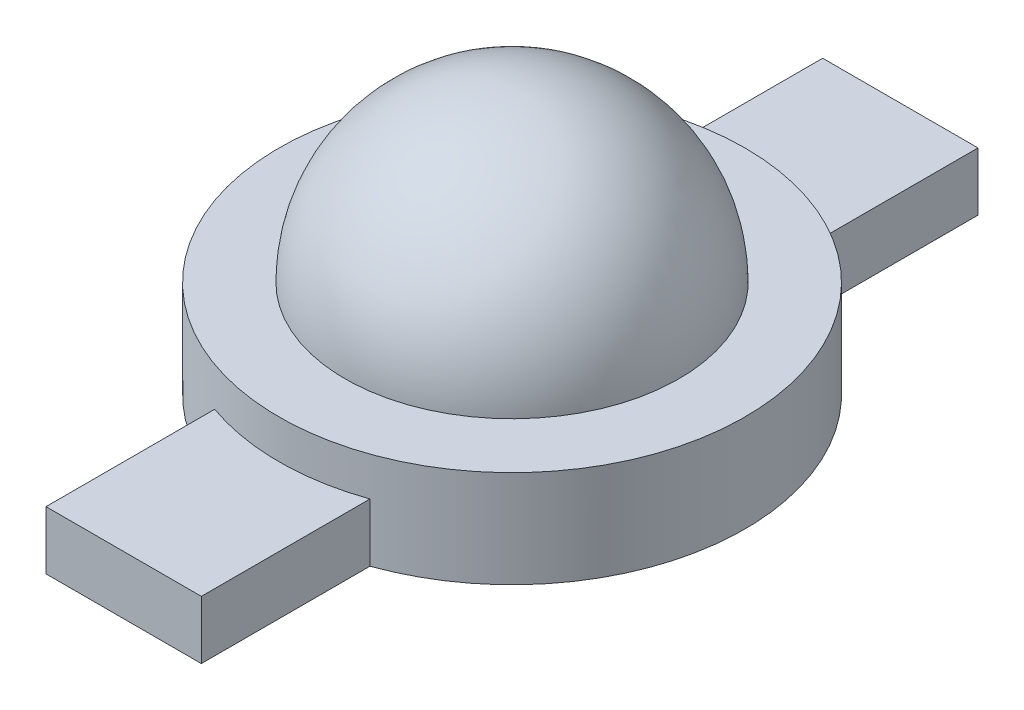
SolidWorks part; units mm, degrees
ref_plane "Front Plane" through (0, 0, 0) normal (0, 0, 1) x (1, 0, 0)
ref_plane "Top Plane" through (0, 0, 0) normal (0, 1, 0) x (1, 0, 0)
ref_plane "Right Plane" through (0, 0, 0) normal (1, 0, 0) x (0, 0, -1)
sketch "Sketch1" plane through (0, 0, 0) normal (1, 0, 0) x (0, 0, -1)
  line L0 (0, 0) -> (4.3, 0) construction
  line L1 (4.3, 0) -> (6, 0)
  line L2 (6, 0) -> (6, -2.5)
  line L3 (6, -2.5) -> (0, -2.5)
  line L4 (0, -2.5) -> (0, 4.3)
  arc A0 (4.3, 0) -> (0, 4.3) centre (0, 0) ccw
  dimension "D3" = 4.3
  dimension "D1" = 6
  dimension "D2" = 2.5
  dimension "D4" = 6.8
revolve "Revolve1" add sketch "Sketch1" angle 360 about L4
sketch "Sketch2" plane through (0, -2.5, 0) normal (0, -1, 0) x (1, 0, 0)
  line L0 (0, 6) -> (0, 10) construction
  line L1 (0, -6) -> (0, -10) construction
  line L2 (0, 10) -> (-2, 10)
  line L3 (-2, 10) -> (-2, 5.6569)
  line L4 (0, 10) -> (2, 10)
  line L5 (2, 10) -> (2, 5.6569)
  line L6 (0, -10) -> (-2, -10)
  line L7 (-2, -10) -> (-2, -5.6569)
  line L8 (0, -10) -> (2, -10)
  line L9 (2, -10) -> (2, -5.6569)
  circle A0 centre (0, 0) radius 6 construction
  arc A1 (-2, 5.6569) -> (2, 5.6569) centre (0, 0) cw
  arc A2 (2, -5.6569) -> (-2, -5.6569) centre (0, 0) cw
  dimension "D1" = 4
  dimension "D2" = 4
  dimension "D3" = 2
  dimension "D4" = 2
  dimension "D5" = 2
  dimension "D6" = 2
extrude "Boss-Extrude1" add sketch "Sketch2" against normal blind 1.5
